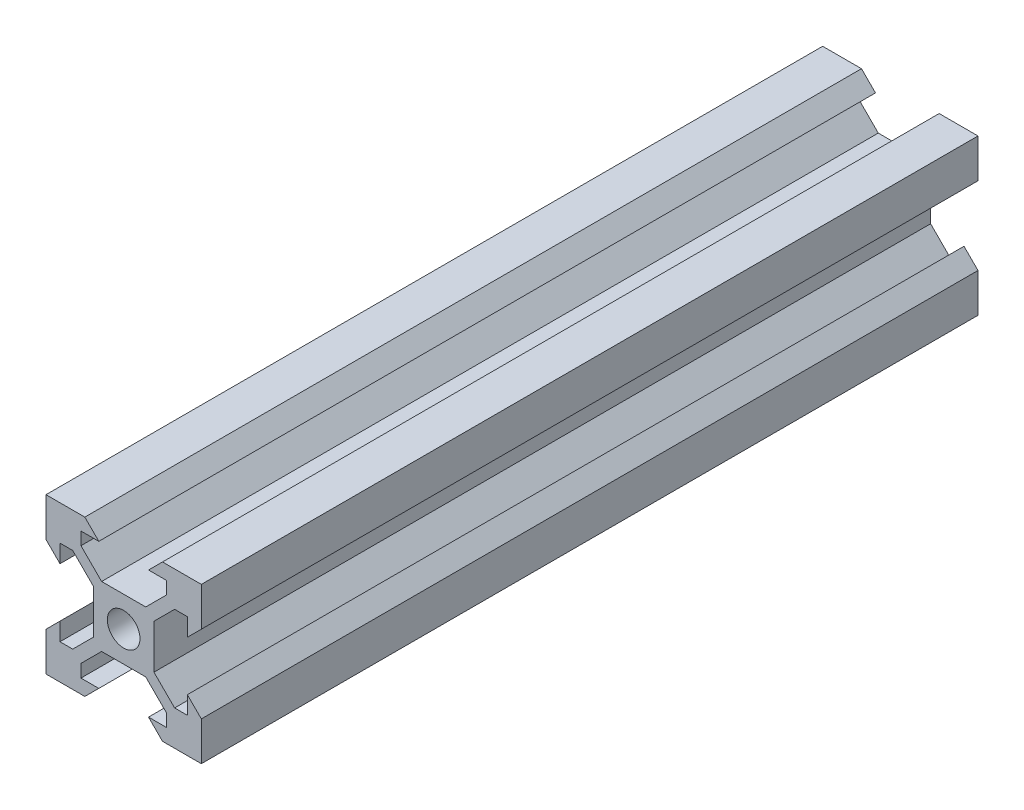
SolidWorks part; units mm, degrees
ref_plane "Front Plane" through (0, 0, 0) normal (0, 0, 1) x (1, 0, 0)
ref_plane "Top Plane" through (0, 0, 0) normal (0, 1, 0) x (1, 0, 0)
ref_plane "Right Plane" through (0, 0, 0) normal (1, 0, 0) x (0, 0, -1)
sketch "Sketch1" plane through (0, 0, 0) normal (0, 0, 1) x (1, 0, 0)
  line L0 (-10, 10) -> (-10, 5)
  line L1 (-10, 5) -> (-8.2, 3.2)
  line L2 (-8.2, 3.2) -> (-8.2, 5.4993)
  line L3 (-8.2, 5.4993) -> (-6.56, 5.4993)
  line L4 (-6.56, 5.4993) -> (-3.9007, 2.84)
  line L5 (-3.9007, 2.84) -> (-3.9007, -2.84)
  line L6 (-3.9007, -2.84) -> (-6.56, -5.4993)
  line L7 (-6.56, -5.4993) -> (-8.2, -5.4993)
  line L8 (-8.2, -5.4993) -> (-8.2, -3.2)
  line L9 (-8.2, -3.2) -> (-10, -5)
  line L10 (-10, -5) -> (-10, -10)
  line L11 (-10, -10) -> (-5, -10)
  line L12 (-5, -10) -> (-3.2, -8.2)
  line L13 (-3.2, -8.2) -> (-5.4993, -8.2)
  line L14 (-5.4993, -8.2) -> (-5.4993, -6.56)
  line L15 (-5.4993, -6.56) -> (-2.84, -3.9007)
  line L16 (-2.84, -3.9007) -> (2.84, -3.9007)
  line L17 (2.84, -3.9007) -> (5.4993, -6.56)
  line L18 (5.4993, -6.56) -> (5.4993, -8.2)
  line L19 (5.4993, -8.2) -> (3.2, -8.2)
  line L20 (3.2, -8.2) -> (5, -10)
  line L21 (5, -10) -> (10, -10)
  line L22 (10, -10) -> (10, -5)
  line L23 (10, -5) -> (8.2, -3.2)
  line L24 (8.2, -3.2) -> (8.2, -5.4993)
  line L25 (8.2, -5.4993) -> (6.56, -5.4993)
  line L26 (6.56, -5.4993) -> (3.9007, -2.84)
  line L27 (3.9007, -2.84) -> (3.9007, 2.84)
  line L28 (3.9007, 2.84) -> (6.56, 5.4993)
  line L29 (6.56, 5.4993) -> (8.2, 5.4993)
  line L30 (8.2, 5.4993) -> (8.2, 3.2)
  line L31 (8.2, 3.2) -> (10, 5)
  line L32 (10, 5) -> (10, 10)
  line L33 (10, 10) -> (5, 10)
  line L34 (5, 10) -> (3.2, 8.2)
  line L35 (3.2, 8.2) -> (5.4993, 8.2)
  line L36 (5.4993, 8.2) -> (5.4993, 6.56)
  line L37 (5.4993, 6.56) -> (2.84, 3.9007)
  line L38 (2.84, 3.9007) -> (-2.84, 3.9007)
  line L39 (-2.84, 3.9007) -> (-5.4993, 6.56)
  line L40 (-5.4993, 6.56) -> (-5.4993, 8.2)
  line L41 (-5.4993, 8.2) -> (-3.2, 8.2)
  line L42 (-3.2, 8.2) -> (-5, 10)
  line L43 (-5, 10) -> (-10, 10)
  circle A0 centre (0, 0) radius 2.1
extrude "Boss-Extrude1" add sketch "Sketch1" against normal blind 100
